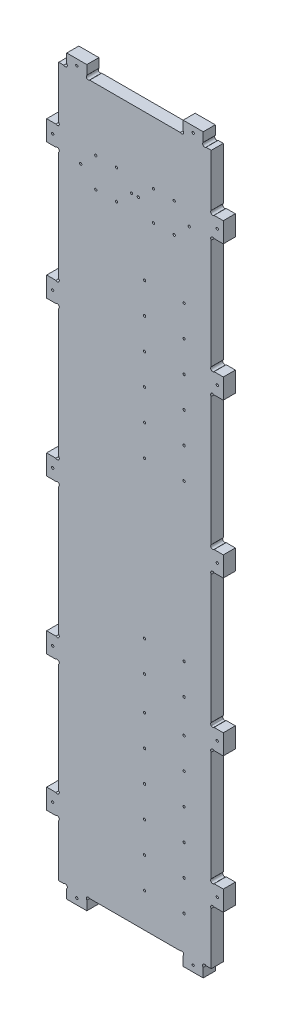
SolidWorks part; units mm, degrees
ref_plane "Front Plane" through (0, 0, 0) normal (0, 0, 1) x (1, 0, 0)
ref_plane "Top Plane" through (0, 0, 0) normal (0, 1, 0) x (1, 0, 0)
ref_plane "Right Plane" through (0, 0, 0) normal (1, 0, 0) x (0, 0, -1)
sketch "Sketch1" plane through (0, 0, 0) normal (0, 0, 1) x (1, 0, 0)
  line L0 (88, -184.1956) -> (-175.75, -184.1956) construction
  line L1 (-175.75, -184.1956) -> (-175.75, 910.041) construction
  line L2 (88, 910.041) -> (-175.75, 910.041) construction
  line L3 (88, -184.1956) -> (88, 910.041) construction
  line L4 (88, -184.1956) -> (-175.75, -184.1956)
  line L5 (-175.75, -184.1956) -> (-175.75, 910.041)
  line L6 (88, 910.041) -> (-175.75, 910.041)
  line L7 (88, -184.1956) -> (88, 910.041)
extrude "Boss-Extrude1" add sketch "Sketch1" along normal blind 18
sketch "Sketch2" plane through (0, 0, 0) normal (0, 0, -1) x (-1, 0, 0)
  line L0 (175.75, 910.041) -> (175.75, -184.1956) construction
  line L5 (175.75, 147.9227) -> (157.75, 147.9227)
  line L6 (175.75, 147.9227) -> (175.75, 347.9227)
  line L7 (157.75, -166.1956) -> (-750.1515, -166.1956) construction
  line L12 (-88, -184.1956) -> (175.75, -184.1956) construction
  line L13 (175.75, -184.1956) -> (145.75, -184.1956)
  line L14 (175.75, -184.1956) -> (175.75, -84.1956)
  line L15 (157.75, -166.1956) -> (145.75, -166.1956)
  line L16 (145.75, -184.1956) -> (145.75, -166.1956)
  line L17 (115.75, -166.1956) -> (43.875, -166.1956)
  line L18 (115.75, -166.1956) -> (115.75, -184.1956)
  line L19 (115.75, -184.1956) -> (-28, -184.1956)
  line L28 (175.75, 362.9227) -> (-88, 362.9227) construction
  line L42 (157.75, 910.041) -> (157.75, -184.1956) construction
  line L44 (157.75, -166.1956) -> (157.75, -84.1956)
  line L45 (157.75, -84.1956) -> (175.75, -84.1956)
  line L47 (175.75, 910.041) -> (175.75, -184.1956) construction
  line L48 (157.75, -54.1956) -> (175.75, -54.1956)
  line L49 (157.75, -54.1956) -> (157.75, 117.9227)
  line L50 (157.75, 117.9227) -> (175.75, 117.9227)
  line L51 (175.75, -54.1956) -> (175.75, 117.9227)
  line L76 (175.75, 347.9227) -> (157.75, 347.9227)
  line L77 (157.75, 147.9227) -> (157.75, 347.9227)
  line L90 (-88, -184.1956) -> (-88, 910.041) construction
  line L91 (43.875, 910.041) -> (43.875, -184.1956) construction
  line L92 (-88, 910.041) -> (175.75, 910.041) construction
  line L93 (-70, 147.9227) -> (-70, 347.9227)
  line L94 (-88, 347.9227) -> (-70, 347.9227)
  line L95 (-88, -54.1956) -> (-88, 117.9227)
  line L96 (-70, 117.9227) -> (-88, 117.9227)
  line L97 (-70, -54.1956) -> (-70, 117.9227)
  line L98 (-70, -54.1956) -> (-88, -54.1956)
  line L99 (-70, -84.1956) -> (-88, -84.1956)
  line L100 (-70, -166.1956) -> (-70, -84.1956)
  line L101 (-28, -166.1956) -> (-28, -184.1956)
  line L102 (-28, -166.1956) -> (43.875, -166.1956)
  line L103 (-58, -184.1956) -> (-58, -166.1956)
  line L104 (-70, -166.1956) -> (-58, -166.1956)
  line L105 (-88, -184.1956) -> (-88, -84.1956)
  line L106 (-88, -184.1956) -> (-58, -184.1956)
  line L107 (-88, 147.9227) -> (-88, 347.9227)
  line L108 (-88, 147.9227) -> (-70, 147.9227)
  line L109 (-88, 577.9227) -> (-70, 577.9227)
  line L110 (-88, 577.9227) -> (-88, 377.9227)
  line L111 (-88, 910.041) -> (-58, 910.041)
  line L112 (-88, 910.041) -> (-88, 810.041)
  line L113 (-70, 892.041) -> (-58, 892.041)
  line L114 (-58, 910.041) -> (-58, 892.041)
  line L115 (-28, 892.041) -> (43.875, 892.041)
  line L116 (-28, 892.041) -> (-28, 910.041)
  line L117 (-70, 892.041) -> (-70, 810.041)
  line L118 (-70, 810.041) -> (-88, 810.041)
  line L119 (-70, 780.041) -> (-88, 780.041)
  line L120 (-70, 780.041) -> (-70, 607.9227)
  line L121 (-70, 607.9227) -> (-88, 607.9227)
  line L122 (-88, 780.041) -> (-88, 607.9227)
  line L123 (-88, 377.9227) -> (-70, 377.9227)
  line L124 (-70, 577.9227) -> (-70, 377.9227)
  line L125 (157.75, 577.9227) -> (157.75, 377.9227)
  line L126 (175.75, 377.9227) -> (157.75, 377.9227)
  line L127 (175.75, 780.041) -> (175.75, 607.9227)
  line L128 (157.75, 607.9227) -> (175.75, 607.9227)
  line L129 (157.75, 780.041) -> (157.75, 607.9227)
  line L130 (157.75, 780.041) -> (175.75, 780.041)
  line L131 (157.75, 810.041) -> (175.75, 810.041)
  line L132 (157.75, 892.041) -> (157.75, 810.041)
  line L134 (115.75, 910.041) -> (-28, 910.041)
  line L135 (115.75, 892.041) -> (115.75, 910.041)
  line L136 (115.75, 892.041) -> (43.875, 892.041)
  line L137 (145.75, 910.041) -> (145.75, 892.041)
  line L138 (157.75, 892.041) -> (145.75, 892.041)
  line L139 (175.75, 910.041) -> (175.75, 810.041)
  line L140 (175.75, 910.041) -> (145.75, 910.041)
  line L141 (175.75, 577.9227) -> (175.75, 377.9227)
  line L142 (175.75, 577.9227) -> (157.75, 577.9227)
  point P3 (79.8125, -166.1956)
  point P39 (7.9375, -166.1956)
  point P88 (7.9375, 892.041)
  point P89 (79.8125, 892.041)
  dimension "D1" = 30
  dimension "D2" = 30
  dimension "D3" = 30
  dimension "D4" = 100
  dimension "D5" = 30
  dimension "D6" = 15
  dimension "D7" = 200
extrude "Cut-Extrude2" cut sketch "Sketch2" against normal blind 18
hole_wizard "M3 Clearance Hole1" positions "Sketch3" profile "Sketch4" hole size "M3" standard "ISO" end condition through all
sketch "Sketch3" plane through (0, 0, 18) normal (0, 0, 1) x (1, 0, 0)
  line L0 (-43.875, -166.1956) -> (-43.875, 892.041) construction
  line L1 (-115.75, -166.1956) -> (28, -166.1956) construction
  line L2 (28, 892.041) -> (-115.75, 892.041) construction
  point P0 (-38.8485, 777.041)
  point P3 (-16.3485, 799.166)
  point P6 (-16.3485, 754.916)
  point P9 (14.6515, 754.916)
  point P12 (14.6515, 799.166)
  point P15 (37.1515, 777.041)
  point P18 (79, 132.9227)
  point P20 (79, 362.9227)
  point P22 (79, 592.9227)
  point P24 (79, 795.041)
  point P26 (79, -69.1956)
  point P37 (43, -175.1956)
  point P39 (43, 901.041)
  point P42 (-130.75, -175.1956)
  point P43 (-166.75, -69.1956)
  point P44 (-166.75, 795.041)
  point P45 (-166.75, 592.9227)
  point P46 (-166.75, 362.9227)
  point P47 (-166.75, 132.9227)
  point P48 (-124.9015, 777.041)
  point P49 (-102.4015, 799.166)
  point P50 (-102.4015, 754.916)
  point P51 (-71.4015, 754.916)
  point P52 (-71.4015, 799.166)
  point P53 (-48.9015, 777.041)
  point P54 (-130.75, 901.041)
sketch "Sketch4" plane through (-38.8485, 777.041, 18) normal (1, 0, 0) x (0, -1, 0)
  line L0 (0, 0) -> (0, 18)
  line L1 (0, 18) -> (1.7, 18)
  line L2 (1.7, 18) -> (1.7, 0)
  line L5 (1.7, 0) -> (0, 0)
  line L11 (0, -6.35) -> (0, 107.95) construction
  dimension "Thru Hole Dia." = 3.4
  dimension "Thru Hole Depth" = 18
hole_wizard "M3 Clearance Hole2" positions "Sketch5" profile "Sketch6" hole size "M3" standard "ISO" end condition through all
sketch "Sketch5" plane through (0, 0, 0) normal (0, 0, -1) x (-1, 0, 0)
  point P0 (-29.503, 536.1338)
  point P2 (-29.503, 582.1338)
  point P4 (29.503, 582.1338)
  point P6 (29.503, 536.1338)
  point P8 (29.503, -23)
  point P10 (29.503, 23)
  point P12 (-29.503, 23)
  point P14 (-29.503, -23)
  point P28 (-29.503, 444.1338)
  point P29 (-29.503, 490.1338)
  point P30 (29.503, 490.1338)
  point P31 (29.503, 444.1338)
  point P32 (29.503, -115)
  point P33 (29.503, -69)
  point P34 (-29.503, -69)
  point P35 (-29.503, -115)
  point P36 (-29.503, 536.1338)
  point P37 (-29.503, 582.1338)
  point P38 (29.503, 582.1338)
  point P39 (29.503, 536.1338)
  point P40 (29.503, -23)
  point P41 (29.503, 23)
  point P42 (-29.503, 23)
  point P43 (-29.503, -23)
  point P44 (-29.503, 628.1338)
  point P45 (-29.503, 674.1338)
  point P46 (29.503, 674.1338)
  point P47 (29.503, 628.1338)
  point P48 (29.503, 69)
  point P49 (29.503, 115)
  point P50 (-29.503, 115)
  point P51 (-29.503, 69)
  point P55 (29.503, 165)
  point P56 (29.503, 211)
  point P57 (-29.503, 211)
  point P58 (-29.503, 165)
  dimension "D1" = 2
  dimension "D2" = 2
  dimension "D3" = 2
sketch "Sketch6" plane through (29.503, 536.1338, 0) normal (1, 0, 0) x (0, 1, 0)
  line L0 (0, 0) -> (0, 18)
  line L1 (0, 18) -> (1.7, 18)
  line L2 (1.7, 18) -> (1.7, 0)
  line L5 (1.7, 0) -> (0, 0)
  line L11 (0, -6.35) -> (0, 107.95) construction
  dimension "Thru Hole Dia." = 3.4
  dimension "Thru Hole Depth" = 18
sketch "Sketch7" plane through (0, 0, 18) normal (0, 0, 1) x (1, 0, 0)
  line L0 (-43.875, -166.1956) -> (-43.875, -145.4341) construction
  line L1 (-115.75, -166.1956) -> (28, -166.1956) construction
  line L2 (-175.75, 362.9227) -> (-196.4431, 362.9227) construction
  line L3 (-175.75, 377.9227) -> (-175.75, 347.9227) construction
  line L4 (-145.75, -166.1956) -> (-157.75, -178.1956) construction
  line L5 (-115.75, -166.1956) -> (-104.3007, -177.6449) construction
  line L6 (28, -166.1956) -> (16.5507, -177.6449) construction
  line L7 (58, -166.1956) -> (70, -178.1956) construction
  line L8 (58, 892.041) -> (70, 904.041) construction
  line L9 (28, 892.041) -> (16.5507, 903.4903) construction
  line L10 (-115.75, 892.041) -> (-104.3007, 903.4903) construction
  line L11 (-145.75, 892.041) -> (-157.75, 904.041) construction
  line L12 (-43.875, 892.041) -> (-43.875, 871.2795) construction
  line L13 (70, 810.041) -> (82, 822.041) construction
  line L14 (88, 795.041) -> (105.8021, 795.041) construction
  line L15 (88, 780.041) -> (88, 810.041) construction
  line L16 (70, 780.041) -> (82, 768.041) construction
  line L17 (70, 607.921) -> (82, 619.921) construction
  line L18 (88, 592.921) -> (105.8021, 592.921) construction
  line L19 (70, 577.921) -> (82, 565.921) construction
  line L20 (70, 147.9244) -> (82, 159.9244) construction
  line L21 (88, 132.9244) -> (105.8021, 132.9244) construction
  line L22 (70, 117.9244) -> (82, 105.9244) construction
  line L23 (70, -54.1956) -> (82, -42.1956) construction
  line L24 (88, -69.1956) -> (105.8021, -69.1956) construction
  line L25 (70, -84.1956) -> (82, -96.1956) construction
  line L26 (70, 377.9227) -> (82, 389.9227) construction
  line L27 (88, 362.9227) -> (105.8021, 362.9227) construction
  line L28 (70, 347.9227) -> (82, 335.9227) construction
  line L29 (-157.75, 347.9227) -> (-169.75, 335.9227) construction
  line L30 (-175.75, 362.9227) -> (-193.5521, 362.9227) construction
  line L31 (-157.75, 377.9227) -> (-169.75, 389.9227) construction
  line L32 (-157.75, -84.1956) -> (-169.75, -96.1956) construction
  line L33 (-175.75, -69.1956) -> (-193.5521, -69.1956) construction
  line L34 (-157.75, -54.1956) -> (-169.75, -42.1956) construction
  line L35 (-157.75, 117.9244) -> (-169.75, 105.9244) construction
  line L36 (-175.75, 132.9244) -> (-193.5521, 132.9244) construction
  line L37 (-157.75, 147.9244) -> (-169.75, 159.9244) construction
  line L38 (-157.75, 577.921) -> (-169.75, 565.921) construction
  line L39 (-175.75, 592.921) -> (-193.5521, 592.921) construction
  line L40 (-157.75, 607.921) -> (-169.75, 619.921) construction
  line L41 (-157.75, 780.041) -> (-169.75, 768.041) construction
  line L42 (-175.75, 795.041) -> (-193.5521, 795.041) construction
  line L43 (-157.75, 810.041) -> (-169.75, 822.041) construction
  circle A0 centre (-147.8713, -168.3169) radius 3
  circle A1 centre (-113.6167, -168.3049) radius 3
  circle A2 centre (25.8667, -168.3049) radius 3
  circle A3 centre (60.1213, -168.3169) radius 3
  circle A4 centre (60.1213, 894.1623) radius 3
  circle A5 centre (25.8667, 894.1503) radius 3
  circle A6 centre (-113.6167, 894.1503) radius 3
  circle A7 centre (-147.8713, 894.1623) radius 3
  circle A8 centre (72.1213, 812.1623) radius 3
  circle A9 centre (72.1213, 777.9196) radius 3
  circle A12 centre (72.1213, 610.0423) radius 3
  circle A13 centre (72.1213, 575.7996) radius 3
  circle A14 centre (72.1213, 150.0458) radius 3
  circle A15 centre (72.1213, 115.8031) radius 3
  circle A16 centre (72.1213, -52.0742) radius 3
  circle A17 centre (72.1213, -86.3169) radius 3
  circle A18 centre (72.1213, 380.044) radius 3
  circle A19 centre (72.1213, 345.8014) radius 3
  circle A20 centre (-159.8713, 345.8014) radius 3
  circle A21 centre (-159.8713, 380.044) radius 3
  circle A22 centre (-159.8713, -86.3169) radius 3
  circle A23 centre (-159.8713, -52.0742) radius 3
  circle A24 centre (-159.8713, 115.8031) radius 3
  circle A25 centre (-159.8713, 150.0458) radius 3
  circle A26 centre (-159.8713, 575.7996) radius 3
  circle A27 centre (-159.8713, 610.0423) radius 3
  circle A28 centre (-159.8713, 777.9196) radius 3
  circle A29 centre (-159.8713, 812.1623) radius 3
  dimension "D1" = 6
  dimension "D2" = 6
  dimension "D3" = 2
extrude "Cut-Extrude3" cut sketch "Sketch7" against normal blind 30
equation "\"osbthickness\"=18"
equation "\"D1@Boss-Extrude1\"=\"osbthickness\""
equation "\"finger\"=30"
equation "\"D1@Sketch2\"=\"finger\""
equation "\"fingerclearance\"=100"
equation "\"D4@Sketch2\"=\"fingerclearance\""
equation "\"D3@Sketch2\"=\"finger\""
equation "\"D5@Sketch2\"=\"finger\""
